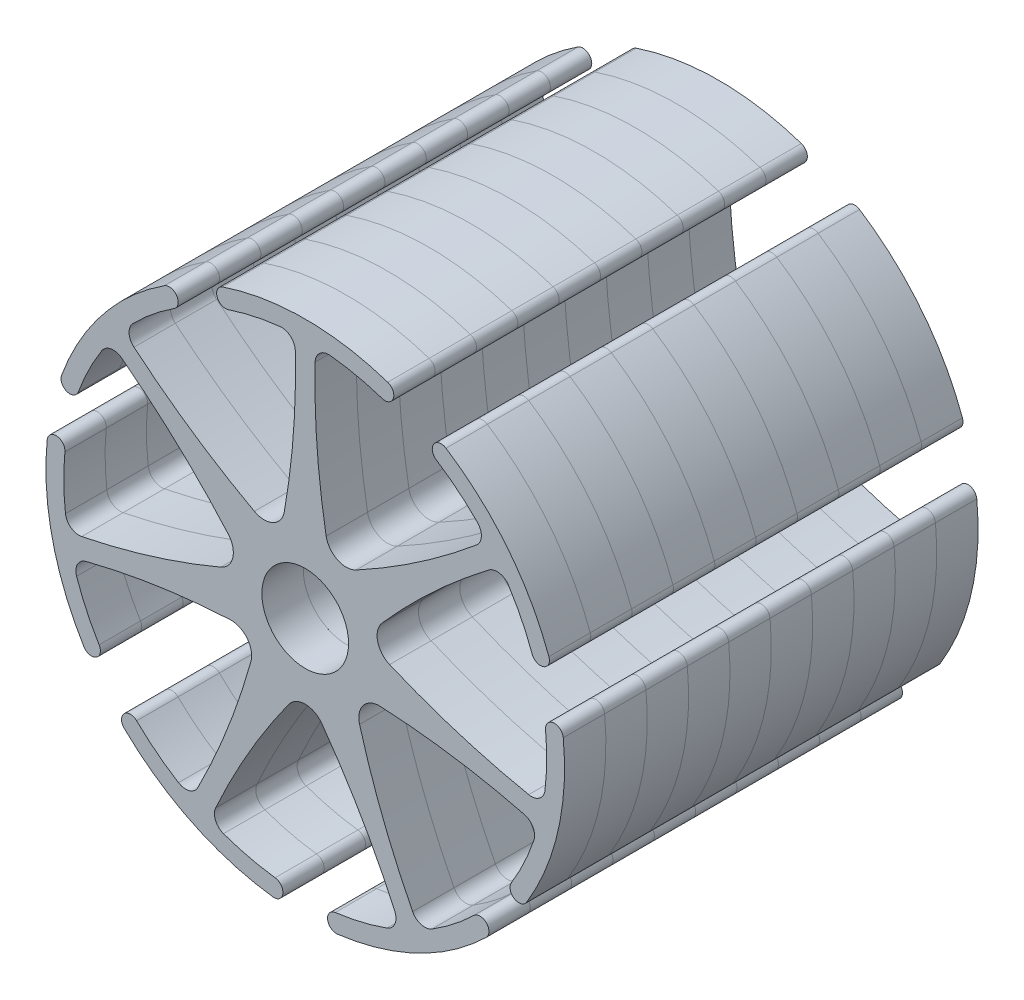
SolidWorks part; units mm, degrees
ref_plane "Front Plane" through (0, 0, 0) normal (0, 0, 1) x (1, 0, 0)
ref_plane "Top Plane" through (0, 0, 0) normal (0, 1, 0) x (1, 0, 0)
ref_plane "Right Plane" through (0, 0, 0) normal (1, 0, 0) x (0, 0, -1)
sketch "Sketch2" plane through (0, 0, 0) normal (0, 0, 1) x (1, 0, 0)
  line L0 (0, 19) -> (-16.4545, -9.5)
  line L1 (-16.4545, -9.5) -> (16.4545, -9.5)
  line L2 (16.4545, -9.5) -> (0, 19)
  line L8 (0, 0) -> (0, 19)
  line L9 (-2.9606, 0) -> (2.9606, 0)
  line L10 (-2.9606, 0) -> (-2.9606, 19)
  line L11 (-2.9606, 19) -> (2.9606, 19)
  line L12 (2.9606, 0) -> (2.9606, 19)
  circle A5 centre (0, 0) radius 19
  arc A6 (5.8388, 17.3939) -> (-5.8388, 17.3939) centre (0, 0) ccw construction
  arc A7 (6.0464, 18.0123) -> (-6.0464, 18.0123) centre (0, 0) ccw
  arc A8 (5.6312, 16.7756) -> (-5.6312, 16.7756) centre (0, 0) ccw
  arc A9 (5.6312, 16.7756) -> (6.0464, 18.0123) centre (5.8388, 17.3939) ccw
  arc A10 (-6.0464, 18.0123) -> (-5.6312, 16.7756) centre (-5.8388, 17.3939) ccw
  arc A11 (-0.7626, 17.6791) -> (-2.9606, 0) centre (-54.0651, 15.3299) cw
  arc A12 (0.7626, 17.6791) -> (2.9606, 0) centre (54.0651, 15.3299) ccw
  point P8 (0, 18.3478)
  dimension "D1" = 38
extrude "Boss-Extrude3" add sketch "Sketch2" against normal blind 3.03 contours L2 A8 L0 L10 L9 L12 | A12 A8 L8 L9
fillet "Fillet1" radius 1 2 edges at (-0.7626, 17.6791, -1.515) (0.7626, 17.6791, -1.515)
sketch "Sketch5" plane through (0, 0, 0) normal (1, 0, 0) x (0, 0, -1)
  line L0 (0, 0) -> (12.727, 0)
pattern_circular "CirPattern1" count 7 over 360 about axis through (0, 0, 0) along (0, 0, 1) of "Boss-Extrude3", "Fillet1"
sketch "Sketch6" plane through (0, 0, -3.03) normal (0, 0, -1) x (-1, 0, 0)
  circle A0 centre (0, 0) radius 3.175
extrude "Cut-Extrude1" cut sketch "Sketch6" against normal blind 82
fillet "Fillet2" radius 1.5 7 edges at (4.3306, 0.9884, -1.515) (3.4728, -2.7695, -1.515) (0, -4.4419, -1.515) (-3.4728, -2.7695, -1.515) (-4.3306, 0.9884, -1.515) (-1.9273, 4.002, -1.515) (1.9273, 4.002, -1.515)
pattern_linear "LPattern1" count 10 spacing 3.03 along (0, 0, 1) of bodies 153
